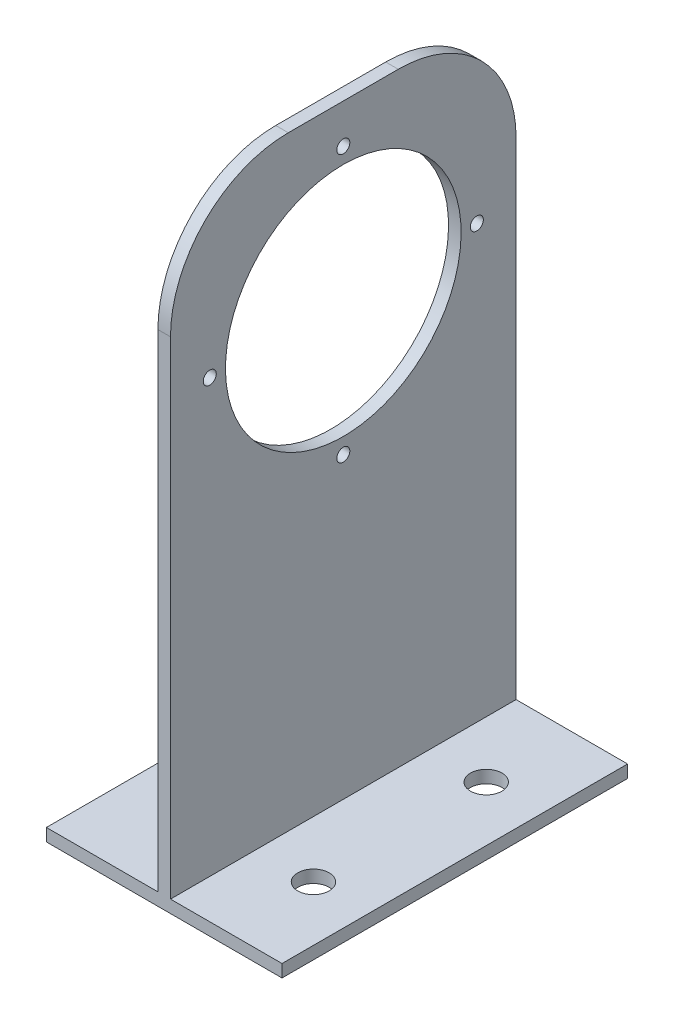
SolidWorks part; units mm, degrees
ref_plane "Front Plane" through (0, 0, 0) normal (0, 0, 1) x (1, 0, 0)
ref_plane "Top Plane" through (0, 0, 0) normal (0, 1, 0) x (1, 0, 0)
ref_plane "Right Plane" through (0, 0, 0) normal (1, 0, 0) x (0, 0, -1)
sketch "Sketch1" plane through (0, 0, 0) normal (0, 0, 1) x (1, 0, 0)
  line L0 (-4, 393) -> (-4, 8)
  line L1 (-4, 8) -> (-75, 8)
  line L2 (-75, 8) -> (-75, 0)
  line L3 (-75, 0) -> (75, 0)
  line L4 (75, 0) -> (75, 8)
  line L5 (75, 8) -> (4, 8)
  line L6 (4, 8) -> (4, 393)
  line L7 (4, 393) -> (-4, 393)
  point P2 (0, 393)
  dimension "D1" = 150
  dimension "D2" = 8
  dimension "D3" = 8
  dimension "D4" = 385
extrude "Boss-Extrude1" add sketch "Sketch1" along normal blind 220
hole_wizard "Ø20.0mm Dowel Hole1" positions "Sketch2" profile "Sketch3" hole size "Ø20.0" standard "ISO" end condition through all
sketch "Sketch2" plane through (0, 0, 0) normal (0, -1, 0) x (-1, 0, 0)
  line L0 (0, 0) -> (0, -220) construction
  line L1 (75, -220) -> (-75, -220) construction
  line L2 (-40, -165) -> (40, -165) construction
  line L3 (40, -165) -> (40, -55) construction
  line L4 (40, -55) -> (-40, -55) construction
  line L5 (-40, -55) -> (-40, -165) construction
  line L6 (75, -110) -> (-75, -110) construction
  line L7 (75, -220) -> (75, 0) construction
  line L8 (-75, -220) -> (-75, 0) construction
  point P0 (-40, -55)
  point P2 (-40, -165)
  point P4 (40, -165)
  point P6 (40, -55)
  point P26 (0, -55)
  point P35 (40, -110)
  dimension "D1" = 80
  dimension "D2" = 110
sketch "Sketch3" plane through (40, 0, 55) normal (1, 0, 0) x (0, 0, -1)
  line L0 (0, 0) -> (0, 393)
  line L1 (0, 393) -> (10, 393)
  line L2 (10, 393) -> (10, 0)
  line L5 (10, 0) -> (0, 0)
  line L11 (0, -6.35) -> (0, 107.95) construction
  dimension "Thru Hole Dia." = 20
  dimension "Thru Hole Depth" = 393
fillet "Fillet1" radius 75 2 edges at (0, 393, 0) (0, 393, 220)
sketch "Sketch4" plane through (4, 0, 0) normal (1, 0, 0) x (0, 0, -1)
  line L0 (-110, 283) -> (-110, 8) construction
  line L1 (-220, 8) -> (0, 8) construction
  line L2 (-145, 393) -> (-75, 393) construction
  circle A0 centre (-110, 283) radius 75
  dimension "D1" = 150
  dimension "D2" = 110
extrude "Cut-Extrude1" cut sketch "Sketch4" against normal through all
hole_wizard "Ø8.0 mm Dowel Holes1" positions "Sketch5" profile "Sketch6" hole size "Ø8.0" standard "ISO" end condition through all
sketch "Sketch5" plane through (4, 0, 0) normal (1, 0, 0) x (0, 0, -1)
  line L0 (-25, 283) -> (-195, 283) construction
  line L2 (-110, 368) -> (-110, 198) construction
  circle A0 centre (-110, 283) radius 75 construction
  point P0 (-110, 368)
  point P2 (-195, 283)
  point P4 (-110, 198)
  point P6 (-25, 283)
  point P17 (-110, 283)
  point P18 (-110, 283)
  dimension "D1" = 170
sketch "Sketch6" plane through (4, 368, 110) normal (0, 1, 0) x (0, 0, -1)
  line L0 (0, 0) -> (0, 79)
  line L1 (0, 79) -> (4.15, 79)
  line L2 (4.15, 79) -> (4.15, 0)
  line L5 (4.15, 0) -> (0, 0)
  line L11 (0, -6.35) -> (0, 107.95) construction
  dimension "Thru Hole Dia." = 8.3
  dimension "Thru Hole Depth" = 79
